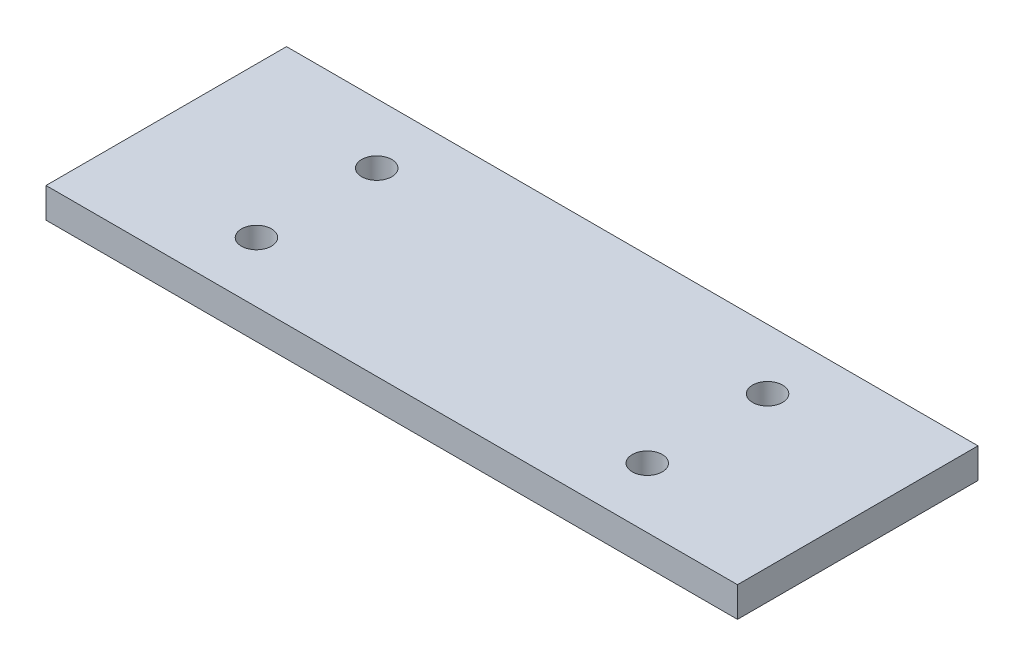
SolidWorks part; units mm, degrees
ref_plane "Front Plane" through (0, 0, 0) normal (0, 0, 1) x (1, 0, 0)
ref_plane "Top Plane" through (0, 0, 0) normal (0, 1, 0) x (1, 0, 0)
ref_plane "Right Plane" through (0, 0, 0) normal (1, 0, 0) x (0, 0, -1)
sketch "Sketch1" plane through (0, 0, 0) normal (0, 1, 0) x (1, 0, 0)
  line L0 (0, 0) -> (42.3333, 0) construction
  line L1 (-57.5, 20) -> (57.5, 20)
  line L2 (-57.5, 20) -> (-57.5, -20)
  line L3 (-57.5, -20) -> (57.5, -20)
  line L4 (57.5, 20) -> (57.5, -20)
  line L5 (-57.5, 20) -> (57.5, -20) construction
  line L6 (-57.5, -20) -> (57.5, 20) construction
  line L7 (0, 0) -> (0, 17.9444) construction
  circle A0 centre (-32.5, 10) radius 2.5
  circle A1 centre (-32.5, -10) radius 2.5
  circle A2 centre (32.5, -10) radius 2.5
  circle A3 centre (32.5, 10) radius 2.5
  point P0 (0, 0)
  dimension "D3" = 5
  dimension "D5" = 65
  dimension "D1" = 115
  dimension "D2" = 40
  dimension "D4" = 10
extrude "Boss-Extrude1" add sketch "Sketch1" along normal blind 5
